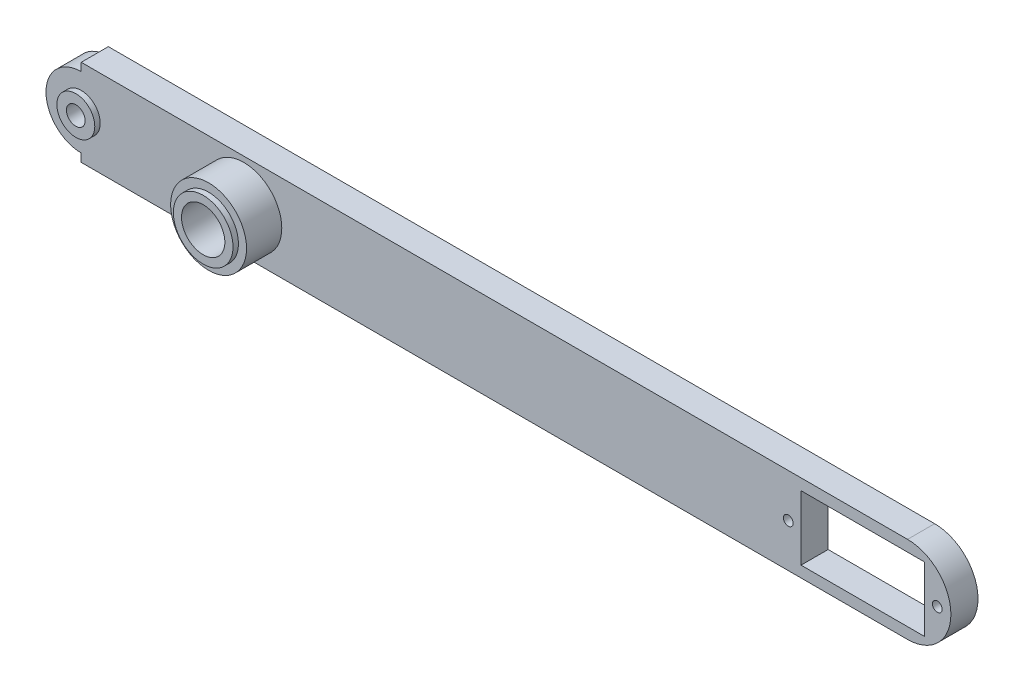
SolidWorks part; units mm, degrees
ref_plane "Front Plane" through (0, 0, 0) normal (0, 0, 1) x (1, 0, 0)
ref_plane "Top Plane" through (0, 0, 0) normal (0, 1, 0) x (1, 0, 0)
ref_plane "Right Plane" through (0, 0, 0) normal (1, 0, 0) x (0, 0, -1)
sketch "Sketch1" plane through (0, 0, 0) normal (0, 0, 1) x (1, 0, 0)
  line L0 (-30, -8) -> (122.45, -8)
  line L1 (122.45, -8) -> (122.45, 8)
  line L2 (122.45, 8) -> (-30, 8)
  line L3 (-30, 8) -> (-30, -8)
extrude "Boss-Extrude1" add sketch "Sketch1" along normal blind 5 from offset 9
sketch "Sketch2" plane through (0, 0, 0) normal (0, 0, 1) x (1, 0, 0)
  circle A0 centre (-30, 0) radius 6.5
extrude "Boss-Extrude2" add sketch "Sketch2" along normal blind 5 from offset 9
sketch "Sketch3" plane through (0, 0, 0) normal (0, 0, 1) x (1, 0, 0)
  circle A0 centre (122.45, 0) radius 8
extrude "Boss-Extrude3" add sketch "Sketch3" along normal blind 5 from offset 9
sketch "Sketch4" plane through (0, 0, 0) normal (0, 0, 1) x (1, 0, 0)
  circle A0 centre (0, 0) radius 7
extrude "Boss-Extrude4" add sketch "Sketch4" along normal blind 11.5 from offset 9
sketch "Sketch5" plane through (0, 0, 0) normal (0, 0, 1) x (1, 0, 0)
  circle A0 centre (0, 0) radius 5.5
extrude "Boss-Extrude5" add sketch "Sketch5" along normal blind 1 from offset 2.5
sketch "Sketch6" plane through (0, 0, 0) normal (0, 0, 1) x (1, 0, 0)
  circle A0 centre (-30, 0) radius 3.5
extrude "Boss-Extrude6" add sketch "Sketch6" along normal blind 1 from offset 4
sketch "Sketch7" plane through (0, 0, 0) normal (0, 0, 1) x (1, 0, 0)
  circle A0 centre (0, 0) radius 4
extrude "Cut-Extrude1" cut sketch "Sketch7" against normal through all and the other way through all
sketch "Sketch8" plane through (0, 0, 0) normal (0, 0, 1) x (1, 0, 0)
  circle A0 centre (-30, 0) radius 1.725
extrude "Cut-Extrude2" cut sketch "Sketch8" against normal through all and the other way through all
sketch "Sketch9" plane through (0, 0, 0) normal (0, 0, 1) x (1, 0, 0)
  line L0 (102.8, -5.95) -> (125.6, -5.95)
  line L1 (125.6, -5.95) -> (125.6, 5.95)
  line L2 (125.6, 5.95) -> (102.8, 5.95)
  line L3 (102.8, 5.95) -> (102.8, -5.95)
extrude "Cut-Extrude3" cut sketch "Sketch9" against normal through all and the other way through all
sketch "Sketch10" plane through (0, 0, 0) normal (0, 0, 1) x (1, 0, 0)
  circle A0 centre (100.45, 0) radius 0.9
  circle A1 centre (127.95, 0) radius 0.9
extrude "Cut-Extrude4" cut sketch "Sketch10" against normal through all and the other way through all
